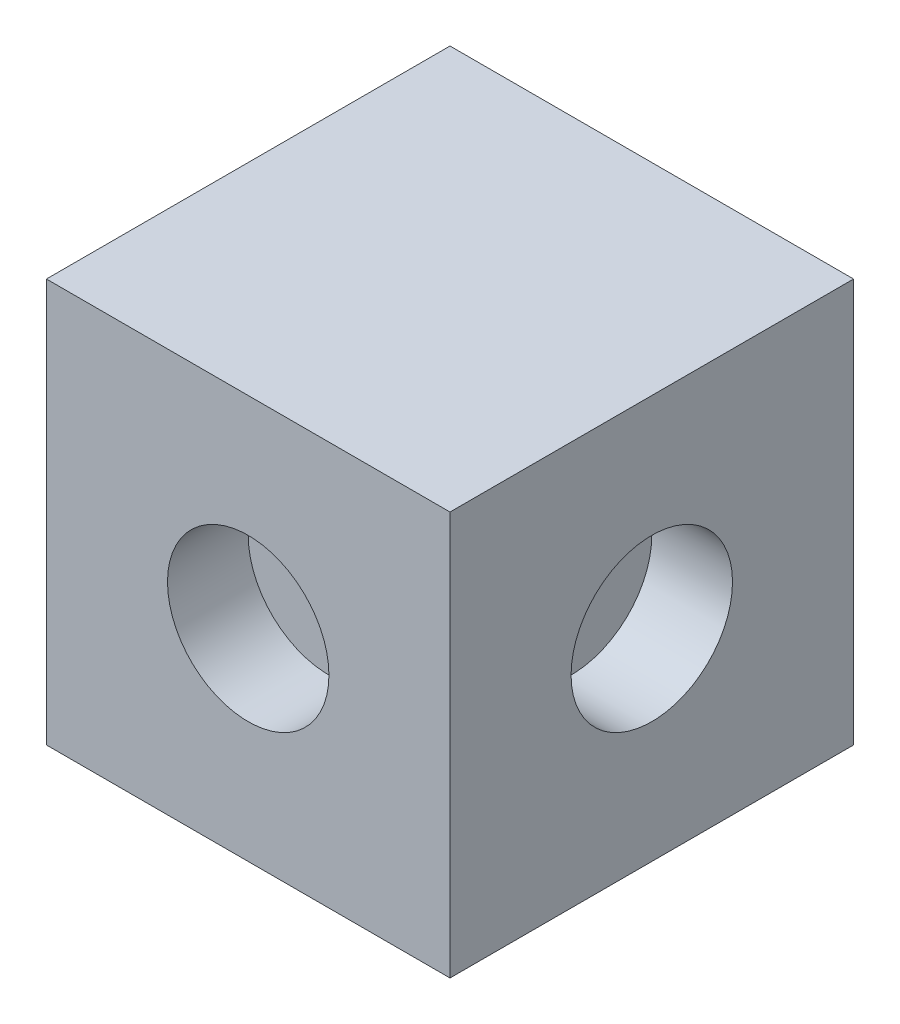
SolidWorks part; units mm, degrees
material "AISI 304"
ref_plane "Front Plane" through (0, 0, 0) normal (0, 0, 1) x (1, 0, 0)
ref_plane "Top Plane" through (0, 0, 0) normal (0, 1, 0) x (1, 0, 0)
ref_plane "Right Plane" through (0, 0, 0) normal (1, 0, 0) x (0, 0, -1)
sketch "Croquis1" plane through (0, 0, 0) normal (0, 1, 0) x (1, 0, 0)
  line L1 (25, -25) -> (-25, -25)
  line L2 (25, -25) -> (25, 25)
  line L3 (25, 25) -> (-25, 25)
  line L4 (-25, -25) -> (-25, 25)
  line L5 (25, -25) -> (-25, 25) construction
  line L6 (25, 25) -> (-25, -25) construction
  point P0 (0, 0)
  dimension "D1" = 50
extrude "Saliente-Extruir1" add sketch "Croquis1" along normal blind 50
sketch "Croquis2" plane through (0, 0, 25) normal (0, 0, 1) x (1, 0, 0)
  line L0 (0, 0) -> (0, 50) construction
  line L1 (-25, 50) -> (25, 50) construction
  circle A0 centre (0, 25) radius 10
  dimension "D1" = 20
extrude "Cortar-Extruir1" cut sketch "Croquis2" against normal blind 10
sketch "Croquis3" plane through (25, 0, 0) normal (1, 0, 0) x (0, 0, -1)
  line L0 (0, 50) -> (0, 0) construction
  line L1 (-25, 50) -> (25, 50) construction
  circle A0 centre (0, 25) radius 10
  dimension "D1" = 20
extrude "Cortar-Extruir2" cut sketch "Croquis3" against normal blind 10
sketch "Croquis4" plane through (0, 0, -25) normal (0, 0, -1) x (-1, 0, 0)
  line L0 (0, 50) -> (0, 0) construction
  line L1 (-25, 50) -> (25, 50) construction
  circle A0 centre (0, 25) radius 10
  dimension "D1" = 20
extrude "Cortar-Extruir3" cut sketch "Croquis4" against normal blind 10
sketch "Croquis5" plane through (-25, 0, 0) normal (-1, 0, 0) x (0, 0, 1)
  line L0 (0, 0) -> (0, 50) construction
  line L1 (-25, 50) -> (25, 50) construction
  circle A0 centre (0, 25) radius 10
  dimension "D1" = 20
extrude "Cortar-Extruir4" cut sketch "Croquis5" against normal blind 10
